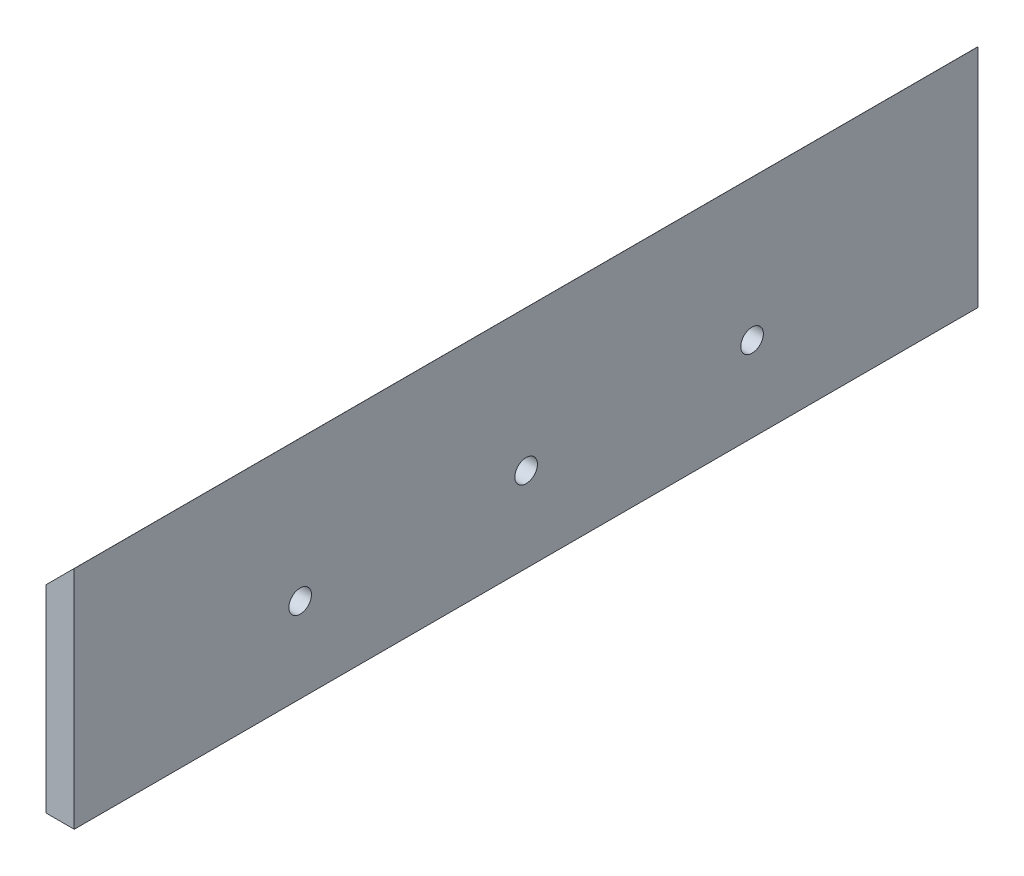
SolidWorks part; units mm, degrees
ref_plane "前基準面" through (0, 0, 0) normal (0, 0, 1) x (1, 0, 0)
ref_plane "上基準面" through (0, 0, 0) normal (0, 1, 0) x (1, 0, 0)
ref_plane "右基準面" through (0, 0, 0) normal (1, 0, 0) x (0, 0, -1)
sketch "草圖1" plane through (0, 0, 0) normal (0, 0, 1) x (1, 0, 0)
  line L0 (203.624, 1001.1769) -> (198.624, 1001.1769)
  line L1 (198.624, 1001.1769) -> (198.624, 1041.1769)
  line L7 (198.624, 1041.1769) -> (203.624, 1041.1629)
  line L8 (203.624, 1041.1629) -> (203.624, 1001.1769)
  dimension "D1" = 40
  dimension "D2" = 5
extrude "填料-伸長1" add sketch "草圖1" along normal blind 160
sketch "Sketch1" plane through (203.624, 0, 0) normal (1, 0, 0) x (0, 0, -1)
  line L0 (0, 1001.1769) -> (0, 1041.1629) construction
  line L1 (-160, 1001.1769) -> (0, 1001.1769) construction
  circle A0 centre (-40, 1016.1769) radius 2
  dimension "D1" = 4
  dimension "D2" = 40
  dimension "D3" = 15
chamfer "Chamfer1" distance 5 angle 45 1 edges at (198.624, 1041.1769, 80)
extrude "Cut-Extrude1" cut sketch "Sketch1" against normal up to surface (5 mm away) up to face at (198.624, 1018.6769, 80)
pattern_linear "LPattern1" count 3 spacing 40 along (0, 0, 1) of "Cut-Extrude1"
